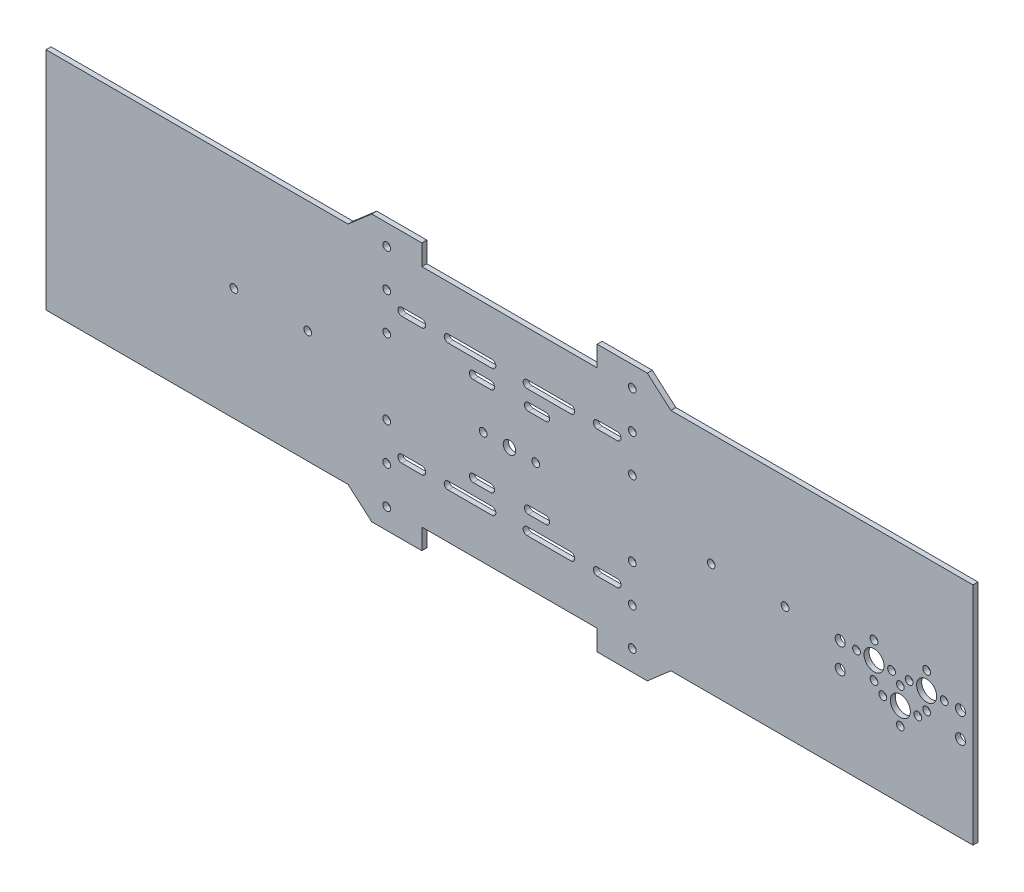
SolidWorks part; units mm, degrees
ref_plane "前视基准面" through (0, 0, 0) normal (0, 0, 1) x (1, 0, 0)
ref_plane "上视基准面" through (0, 0, 0) normal (0, 1, 0) x (1, 0, 0)
ref_plane "右视基准面" through (0, 0, 0) normal (1, 0, 0) x (0, 0, -1)
other "Configuration Table"
sketch "草图1" plane through (0, 0, 0) normal (0, 0, 1) x (1, 0, 0)
  line L0 (0, 0) -> (0, -160.6842) construction
  line L5 (0, 0) -> (87.0965, 0) construction
  line L14 (49, -45) -> (50.55, -45)
  line L16 (49, -45) -> (49, -15) construction
  line L17 (7.5, -17.8) -> (14.5, -17.8) construction
  line L18 (7.5, -16.25) -> (14.5, -16.25)
  line L19 (7.5, -19.35) -> (14.5, -19.35)
  line L20 (7, -25.4) -> (24.5, -25.4) construction
  line L21 (7, -23.85) -> (24.5, -23.85)
  line L22 (7, -26.95) -> (24.5, -26.95)
  line L23 (35, -25.4) -> (43, -25.4) construction
  line L24 (35, -23.85) -> (43, -23.85)
  line L25 (35, -26.95) -> (43, -26.95)
  line L26 (-35, 45) -> (35, 45)
  line L27 (-35, -45) -> (35, -45)
  line L28 (64.4312, 45) -> (185, 45)
  line L29 (185, 45) -> (185, -45)
  line L30 (-49, -45) -> (-49, -15) construction
  line L31 (185, -45) -> (64.4312, -45)
  line L32 (-185, -45) -> (-64.4312, -45)
  line L33 (-185, 45) -> (-185, -45)
  line L39 (-35, -25.4) -> (-43, -25.4) construction
  line L40 (-35, -23.85) -> (-43, -23.85)
  line L41 (-35, -26.95) -> (-43, -26.95)
  line L42 (-7, -25.4) -> (-24.5, -25.4) construction
  line L43 (-7, -23.85) -> (-24.5, -23.85)
  line L44 (-7, -26.95) -> (-24.5, -26.95)
  line L45 (-7.5, -17.8) -> (-14.5, -17.8) construction
  line L46 (-7.5, -16.25) -> (-14.5, -16.25)
  line L47 (-7.5, -19.35) -> (-14.5, -19.35)
  line L48 (-73.8624, 45) -> (-185, 45)
  line L49 (35, 53.2) -> (35, 45)
  line L50 (-55, 53.2) -> (-35, 53.2)
  line L51 (-49, 45) -> (-49, 15) construction
  line L52 (-35, 53.2) -> (-35, 45)
  line L53 (-55, 53.2) -> (-64.4312, 45)
  line L54 (-73.8624, 45) -> (-64.4312, 45)
  line L55 (55, 53.2) -> (35, 53.2)
  line L56 (49, 45) -> (49, 15) construction
  line L57 (55, 53.2) -> (64.4312, 45)
  line L58 (55, -53.2) -> (64.4312, -45)
  line L59 (55, -53.2) -> (35, -53.2)
  line L60 (35, -53.2) -> (35, -45)
  line L70 (-7.5, 17.8) -> (-14.5, 17.8) construction
  line L71 (-7.5, 16.25) -> (-14.5, 16.25)
  line L72 (-7.5, 19.35) -> (-14.5, 19.35)
  line L73 (-7, 25.4) -> (-24.5, 25.4) construction
  line L74 (-7, 23.85) -> (-24.5, 23.85)
  line L75 (-7, 26.95) -> (-24.5, 26.95)
  line L76 (-35, 25.4) -> (-43, 25.4) construction
  line L77 (-35, 23.85) -> (-43, 23.85)
  line L78 (-35, 26.95) -> (-43, 26.95)
  line L79 (35, 25.4) -> (43, 25.4) construction
  line L80 (35, 23.85) -> (43, 23.85)
  line L81 (35, 26.95) -> (43, 26.95)
  line L82 (7, 25.4) -> (24.5, 25.4) construction
  line L83 (7, 23.85) -> (24.5, 23.85)
  line L84 (7, 26.95) -> (24.5, 26.95)
  line L85 (7.5, 17.8) -> (14.5, 17.8) construction
  line L86 (7.5, 16.25) -> (14.5, 16.25)
  line L87 (7.5, 19.35) -> (14.5, 19.35)
  line L88 (-35, -53.2) -> (-35, -45)
  line L89 (-55, -53.2) -> (-35, -53.2)
  line L90 (-55, -53.2) -> (-64.4312, -45)
  arc A18 (50.55, -45) -> (47.45, -45) centre (49, -45) ccw
  circle A19 centre (49, -30) radius 1.55
  circle A20 centre (49, -15) radius 1.55
  circle A21 centre (0, 0) radius 10.5 construction
  circle A22 centre (10.5, 0) radius 1.55
  arc A23 (7.5, -16.25) -> (7.5, -19.35) centre (7.5, -17.8) ccw
  arc A24 (14.5, -19.35) -> (14.5, -16.25) centre (14.5, -17.8) ccw
  arc A25 (7, -23.85) -> (7, -26.95) centre (7, -25.4) ccw
  arc A26 (24.5, -26.95) -> (24.5, -23.85) centre (24.5, -25.4) ccw
  arc A27 (35, -23.85) -> (35, -26.95) centre (35, -25.4) ccw
  arc A28 (43, -26.95) -> (43, -23.85) centre (43, -25.4) ccw
  circle A39 centre (-10.5, 0) radius 1.55
  circle A40 centre (-49, -15) radius 1.55
  circle A41 centre (-49, -30) radius 1.55
  arc A42 (-50.55, -45) -> (-47.45, -45) centre (-49, -45) cw
  arc A56 (-35, -23.85) -> (-35, -26.95) centre (-35, -25.4) cw
  arc A57 (-43, -26.95) -> (-43, -23.85) centre (-43, -25.4) cw
  arc A58 (-7, -23.85) -> (-7, -26.95) centre (-7, -25.4) cw
  arc A59 (-24.5, -26.95) -> (-24.5, -23.85) centre (-24.5, -25.4) cw
  arc A60 (-7.5, -16.25) -> (-7.5, -19.35) centre (-7.5, -17.8) cw
  arc A61 (-14.5, -19.35) -> (-14.5, -16.25) centre (-14.5, -17.8) cw
  circle A62 centre (-49, 45) radius 1.55
  circle A63 centre (49, 45) radius 1.55
  circle A78 centre (-49, 30) radius 1.55
  circle A79 centre (-49, 15) radius 1.55
  circle A90 centre (49, 15) radius 1.55
  circle A91 centre (49, 30) radius 1.55
  arc A92 (50.55, 45) -> (47.45, 45) centre (49, 45) cw
  arc A109 (-7.5, 16.25) -> (-7.5, 19.35) centre (-7.5, 17.8) ccw
  arc A110 (-14.5, 19.35) -> (-14.5, 16.25) centre (-14.5, 17.8) ccw
  arc A111 (-7, 23.85) -> (-7, 26.95) centre (-7, 25.4) ccw
  arc A112 (-24.5, 26.95) -> (-24.5, 23.85) centre (-24.5, 25.4) ccw
  arc A113 (-35, 23.85) -> (-35, 26.95) centre (-35, 25.4) ccw
  arc A114 (-43, 26.95) -> (-43, 23.85) centre (-43, 25.4) ccw
  arc A115 (35, 23.85) -> (35, 26.95) centre (35, 25.4) cw
  arc A116 (43, 26.95) -> (43, 23.85) centre (43, 25.4) cw
  arc A117 (7, 23.85) -> (7, 26.95) centre (7, 25.4) cw
  arc A118 (24.5, 26.95) -> (24.5, 23.85) centre (24.5, 25.4) cw
  arc A119 (7.5, 16.25) -> (7.5, 19.35) centre (7.5, 17.8) cw
  arc A120 (14.5, 19.35) -> (14.5, 16.25) centre (14.5, 17.8) cw
  circle A121 centre (49, -45) radius 1.55
  circle A122 centre (-49, -45) radius 1.55
  circle A123 centre (-80.5, 0) radius 1.55
  circle A124 centre (-110, 0) radius 1.55
  circle A125 centre (80.5, 0) radius 1.55
  circle A126 centre (110, 0) radius 1.55
  circle A127 centre (132, -0.8) radius 2
  circle A128 centre (132, -10.8) radius 2
  circle A129 centre (145.5, -0.8) radius 4
  circle A130 centre (145.5, 6.2) radius 1.55
  circle A131 centre (138.5, -0.8) radius 1.55
  circle A132 centre (152.5, -0.8) radius 1.55
  circle A141 centre (145.5, -7.8) radius 1.55
  circle A142 centre (149, -11.3) radius 1.55
  circle A143 centre (156, -4.3) radius 1.55
  circle A144 centre (180, -10.8) radius 2
  circle A145 centre (180, -0.8) radius 2
  circle A146 centre (156, -18.3) radius 1.55
  circle A147 centre (163, -11.3) radius 1.55
  circle A148 centre (156, -11.3) radius 4
  circle A149 centre (166.5, -0.8) radius 4
  circle A150 centre (159.5, -0.8) radius 1.55
  circle A151 centre (166.5, -7.8) radius 1.55
  circle A152 centre (173.5, -0.8) radius 1.55
  circle A153 centre (166.5, 6.2) radius 1.55
  circle A154 centre (0, 0) radius 2.5
  point P59 (11, -17.8)
  point P64 (15.75, -25.4)
  point P71 (39, -25.4)
  point P138 (55, 0)
  point P143 (-39, -25.4)
  point P150 (-15.75, -25.4)
  point P157 (-11, -17.8)
  point P266 (-55, 0)
  point P268 (-11, 17.8)
  point P275 (-15.75, 25.4)
  point P282 (-39, 25.4)
  point P293 (39, 25.4)
  point P300 (15.75, 25.4)
  point P307 (11, 17.8)
  dimension "D5" = 3.1
  dimension "D16" = 21
  dimension "D23" = 1.55
  dimension "D24" = 1.55
  dimension "D25" = 1.55
  dimension "D6" = 3.1
  dimension "D3" = 370
  dimension "D4" = 20
  dimension "D13" = 90
  dimension "D14" = 30
  dimension "D15" = 60
  dimension "D17" = 15
  dimension "D18" = 29
  dimension "D19" = 14
  dimension "D20" = 49
  dimension "D21" = 70
  dimension "D22" = 86
  dimension "D26" = 17.8
  dimension "D27" = 25.4
  dimension "D28" = 49
extrude "凸台-拉伸1" add sketch "草图1" along normal blind 2
